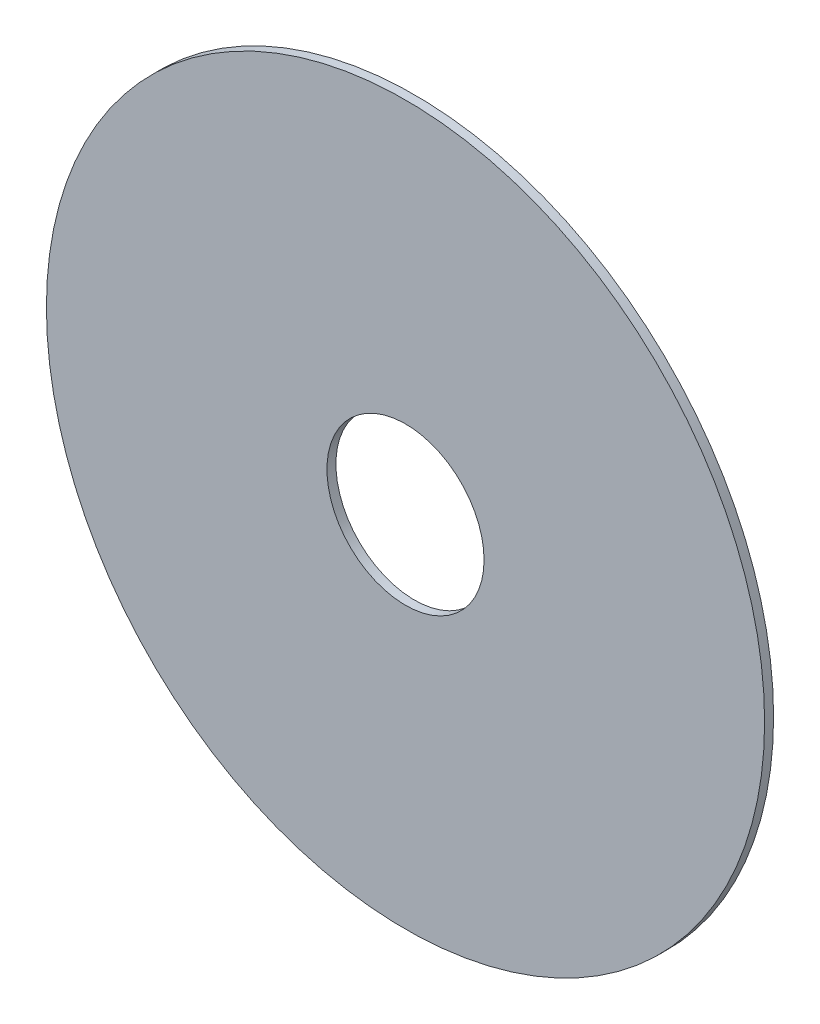
SolidWorks part; units mm, degrees
ref_plane "Front" through (0, 0, 0) normal (0, 0, 1) x (1, 0, 0)
ref_plane "Top" through (0, 0, 0) normal (0, 1, 0) x (1, 0, 0)
ref_plane "Right" through (0, 0, 0) normal (1, 0, 0) x (0, 0, -1)
sketch "Sketch1" plane through (0, 0, 0) normal (0, 0, 1) x (1, 0, 0)
  circle A0 centre (0, 0) radius 80
extrude "Boss-Extrude1" add sketch "Sketch1" along normal blind 2
sketch "Sketch3" plane through (0, 0, 2) normal (0, 0, 1) x (1, 0, 0)
  circle A0 centre (0, 0) radius 17.5
extrude "Cut-Extrude1" cut sketch "Sketch3" against normal blind 2 contours A0
